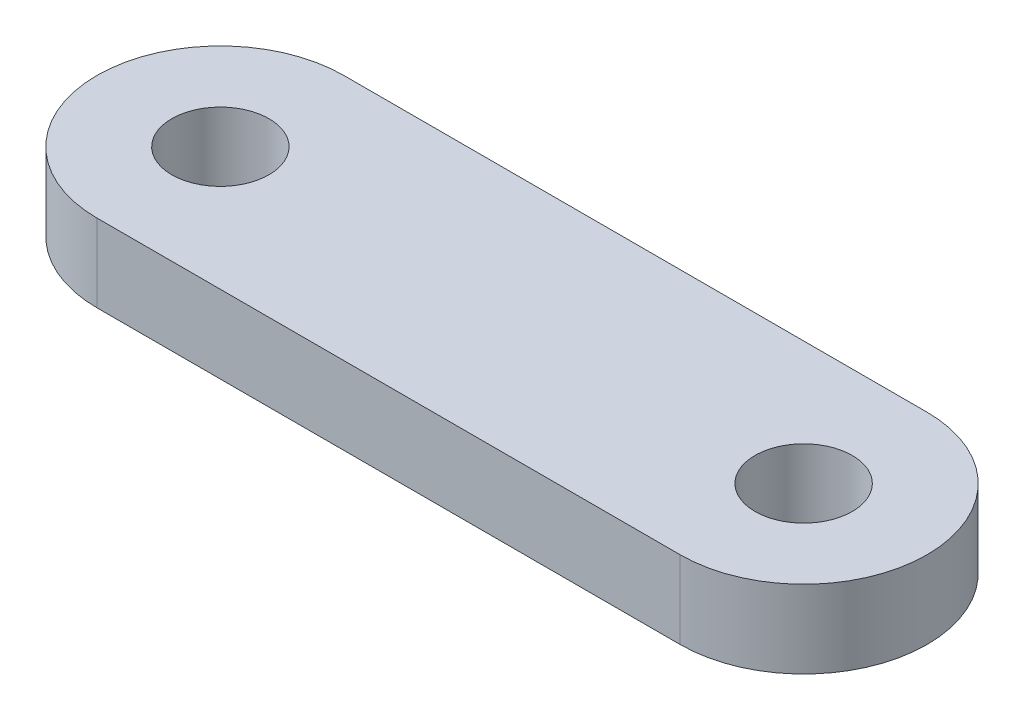
SolidWorks part; units mm, degrees
material "AISI 1020"
ref_plane "Plano superior" through (0, 0, 0) normal (0, 0, 1) x (1, 0, 0)
ref_plane "Plano frontal" through (0, 0, 0) normal (0, 1, 0) x (1, 0, 0)
ref_plane "Plano direito" through (0, 0, 0) normal (1, 0, 0) x (0, 0, -1)
sketch "Esboço1" plane through (0, 0, 0) normal (0, 1, 0) x (1, 0, 0)
  line L0 (-30, 0) -> (30, 0) construction
  line L1 (0, 0) -> (0, 21.3411) construction
  line L2 (-30, 12.7) -> (30, 12.7)
  line L3 (-30, -12.7) -> (30, -12.7)
  circle A0 centre (30, 0) radius 5
  circle A1 centre (-30, 0) radius 5
  arc A2 (-30, 12.7) -> (-30, -12.7) centre (-30, 0) ccw
  arc A3 (30, 12.7) -> (30, -12.7) centre (30, 0) cw
  dimension "D1" = 10
  dimension "D3" = 10
  dimension "D5" = 25.4
  dimension "D4" = 30
extrude "Ressalto-extrusão1" add sketch "Esboço1" along normal mid plane 8
